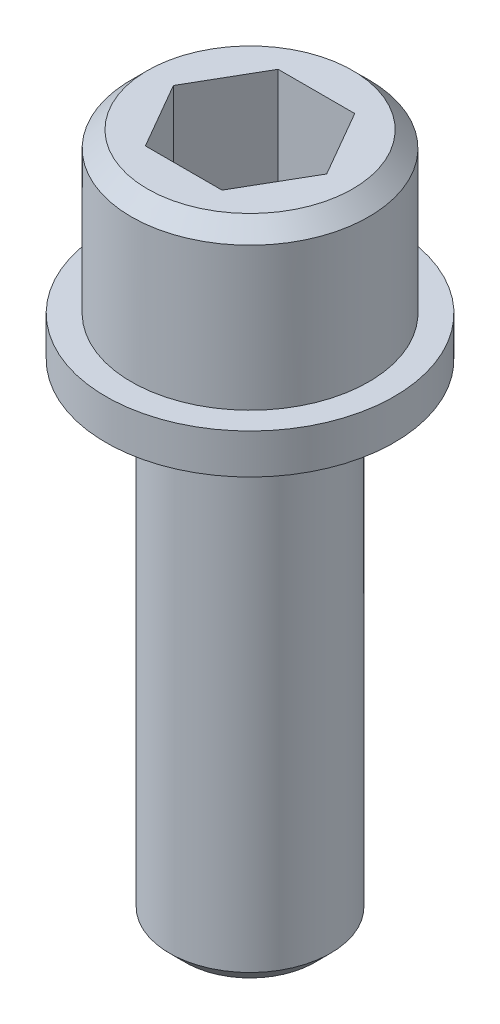
SolidWorks part; units mm, degrees
ref_plane "Alzado" through (0, 0, 0) normal (0, 0, 1) x (1, 0, 0)
ref_plane "Planta" through (0, 0, 0) normal (0, 1, 0) x (1, 0, 0)
ref_plane "Vista lateral" through (0, 0, 0) normal (1, 0, 0) x (0, 0, -1)
sketch "Croquis1" plane through (0, 0, 0) normal (0, 0, 1) x (1, 0, 0)
  line L0 (0, 0) -> (0, 41.275) construction
  line L1 (0, 41.275) -> (7.112, 41.275)
  line L2 (7.112, 41.275) -> (7.112, 31.75)
  line L3 (7.112, 31.75) -> (8.636, 31.75)
  line L4 (8.636, 31.75) -> (8.636, 29.3624)
  line L5 (8.636, 29.3624) -> (4.826, 29.3624)
  line L6 (4.826, 29.3624) -> (4.826, 0)
  line L7 (4.826, 0) -> (0, 0)
  line L8 (0, 0) -> (0, 41.275)
  dimension "D1" = 9.652
  dimension "D2" = 14.224
  dimension "D3" = 17.272
  dimension "D4" = 41.275
  dimension "D5" = 9.525
  dimension "D6" = 2.3876
revolve "Revolución1" add sketch "Croquis1" angle 360 about L0
sketch "Croquis2" plane through (0, 41.275, 0) normal (0, 1, 0) x (1, 0, 0)
  line L1 (-2.295, 3.9751) -> (-4.5901, 0)
  line L2 (-4.5901, 0) -> (-2.295, -3.9751)
  line L3 (-2.295, -3.9751) -> (2.295, -3.9751)
  line L4 (2.295, -3.9751) -> (4.5901, 0)
  line L5 (4.5901, 0) -> (2.295, 3.9751)
  line L6 (2.295, 3.9751) -> (-2.295, 3.9751)
  circle A0 centre (0, 0) radius 3.9751 construction
  dimension "D1" = 7.9502
extrude "Cortar-Extruir1" cut sketch "Croquis2" against normal blind 6.35
chamfer "Chaflán1" distance 0.9652 angle 45 2 edges at (0, 0, -4.826) (0, 41.275, -7.112)
